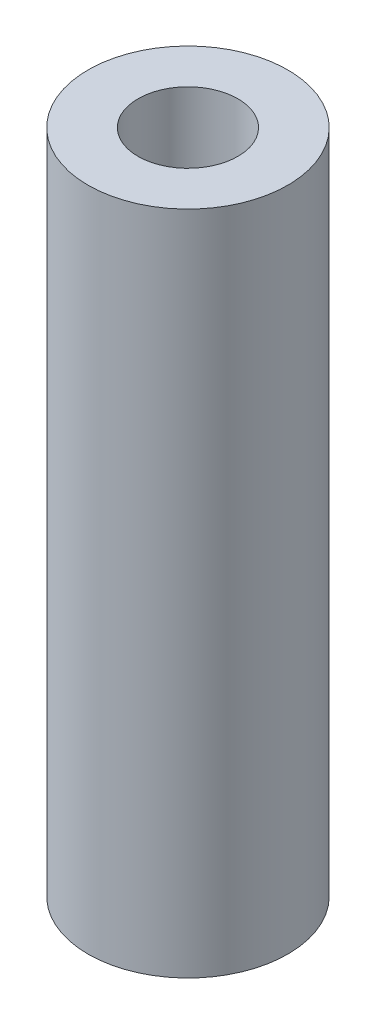
SolidWorks part; units mm, degrees
material "6061 合金"
ref_plane "前视基准面" through (0, 0, 0) normal (0, 0, 1) x (1, 0, 0)
ref_plane "上视基准面" through (0, 0, 0) normal (0, 1, 0) x (1, 0, 0)
ref_plane "右视基准面" through (0, 0, 0) normal (1, 0, 0) x (0, 0, -1)
other "Configuration Table"
sketch "草图1" plane through (0, 0, 0) normal (0, 1, 0) x (1, 0, 0)
  circle A0 centre (0, 0) radius 3
  circle A1 centre (0, 0) radius 1.5
  dimension "D1" = 6
  dimension "D2" = 3
extrude "凸台-拉伸1" add sketch "草图1" along normal blind 20
